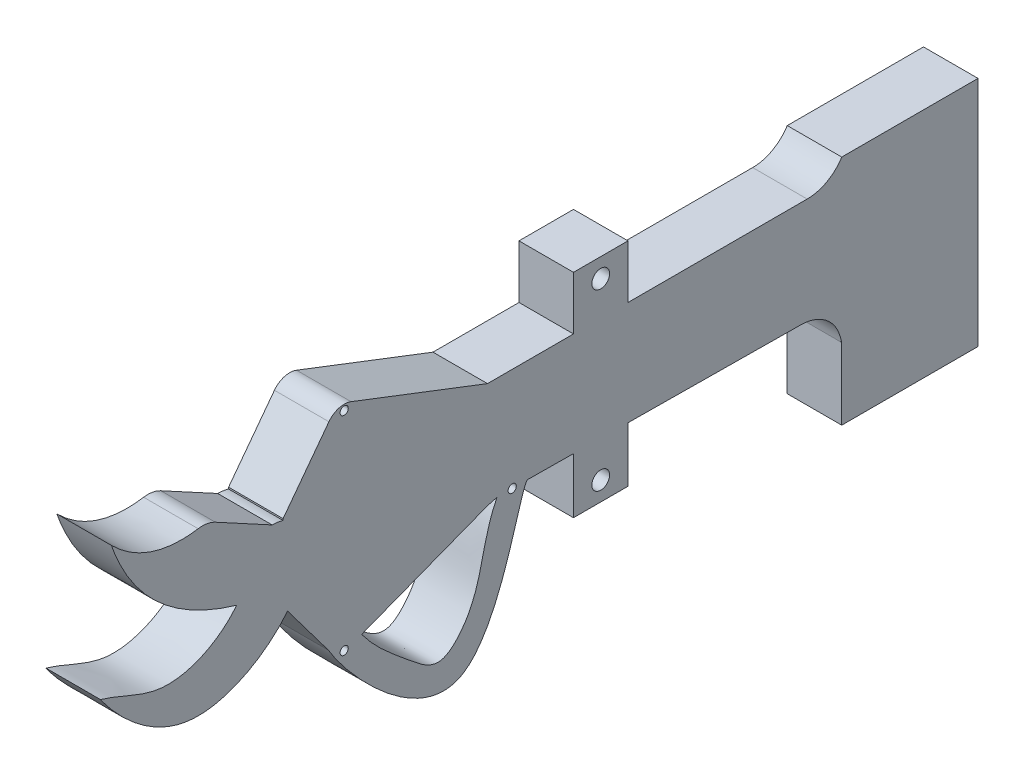
SolidWorks part; units mm, degrees
ref_plane "Front Plane" through (0, 0, 0) normal (0, 0, 1) x (1, 0, 0)
ref_plane "Top Plane" through (0, 0, 0) normal (0, 1, 0) x (1, 0, 0)
ref_plane "Right Plane" through (0, 0, 0) normal (1, 0, 0) x (0, 0, -1)
ref_plane "Plane4" through (70, 0, 0) normal (1, 0, 0) x (0, 0, -1)
sketch "Sketch15" plane through (70, 0, 0) normal (1, 0, 0) x (0, 0, -1)
  line L0 (-98.44, 39) -> (-98.44, -39)
  line L1 (-98.44, -39) -> (-78.44, -39)
  line L2 (0, -32.5439) -> (0, -58.81)
  line L3 (-78.44, -39) -> (-78.44, 39)
  line L4 (-78.44, 39) -> (-98.44, 39)
  line L5 (50, 26.41) -> (50, -58.81)
  line L6 (-88.44, 39) -> (-88.44, -39) construction
  line L7 (-229.8609, 25.2996) -> (-209, 14)
  line L8 (-205, -13.4164) -> (-205, -14)
  line L9 (-205, -14) -> (-203.3467, -16.1994)
  line L37 (0, 26.41) -> (50, 26.41)
  line L39 (50, -58.81) -> (0, -58.81)
  line L44 (0, -32.5439) -> (0, -32.1716)
  line L46 (-180.0653, 38.7034) -> (-130, 19.41)
  line L48 (-205, 14) -> (-188.1778, 36.3778)
  line L49 (-205, 13.4164) -> (-205, 14)
  line L50 (-205, -14) -> (-205, -13.4164)
  line L51 (-188.1778, -36.3778) -> (-205, -14)
  line L52 (-130, -19.41) -> (-180.0653, -38.7034)
  line L56 (-126.4914, -18.4594) -> (-122.4285, -18.4594)
  line L57 (-119.4285, -18.4594) -> (-115.3655, -18.4594)
  line L58 (-188.3397, -36.1623) -> (-188.1778, -36.3778)
  line L59 (-180.0653, -38.7034) -> (-176.1714, -37.2028)
  line L60 (-130, 19.41) -> (-12.6886, 19.41)
  line L61 (-115.3655, -18.4594) -> (-15, -19.41)
  line L63 (0, -32.1716) -> (0, -32.5439)
  line L64 (-130, -19.41) -> (-126.4914, -18.4594)
  circle A0 centre (-209, 0) radius 14
  circle A1 centre (-88.44, 32) radius 3.25
  circle A2 centre (-88.44, -32) radius 3.25
  circle A3 centre (-182.5824, 37.1303) radius 1.5
  circle A4 centre (-182.5824, -39.1197) radius 1.5
  arc A8 (-229.8609, 25.2996) -> (-236.1722, 26.3861) centre (-234.6237, 16.5067) ccw
  arc A10 (-181.0865, -39.0099) -> (-180.0653, -38.7034) centre (-182.5824, -32.1716) ccw
  circle A20 centre (-120.9285, -18.4594) radius 1.5
  arc A21 (-180.0653, 38.7034) -> (-184.5114, 38.9005) centre (-182.5824, 32.1716) ccw
  arc A22 (-184.5114, 38.9005) -> (-188.1778, 36.3778) centre (-182.5824, 32.1716) ccw
  arc A26 (-188.1778, -36.3778) -> (-184.0784, -39.0099) centre (-182.5824, -32.1716) ccw
  arc A27 (-181.0865, -39.0099) -> (-180.0653, -38.7034) centre (-182.5824, -32.1716) ccw
  arc A28 (-122.4285, -18.4594) -> (-119.4285, -18.4594) centre (-120.9285, -18.4594) ccw
  arc A29 (-188.1778, -36.3778) -> (-184.0784, -39.0099) centre (-182.5824, -32.1716) ccw
  parabola Q1 (-222.0767, -5) -> (-268, 37) focus (-233.1222, 34.7362) apex (-255.3029, 14.9374)
  spline S3 degree 3 poles (-268, 37) (-259.1388, 28.0952) (-248.2711, 24.4897) (-236.1722, 26.3861) knots 0 0 0 0 0.920407 0.920407 0.920407 0.920407
  spline S4 degree 3 poles (-272, -10) (-264.5451, -12.0829) (-248.031, -22.7664) (-228.2351, -13.0001) (-222.0767, -5) knots 0 0 0 0 0.427591 1 1 1 1
  spline S5 degree 3 poles (-203.3467, -16.1994) (-211.2266, -26.0808) (-240.3414, -42.6421) (-264.5448, -20.589) (-272, -10) knots 0 0 0 0 0.497871 1 1 1 1
  spline S10 degree 3 poles (-115.3655, -18.4594) (-118.3377, -20.6676) (-132.1424, -105.1833) (-182.5001, -46.5279) (-188.3397, -36.1623) knots 0.03269 0.03269 0.03269 0.03269 0.488323 0.982304 0.982304 0.982304 0.982304
  spline S11 degree 3 poles (-176.1714, -37.2028) (-171.1396, -44.05) (-162.8, -50.6114) (-148.0822, -63.1004) (-130.812, -46.5745) (-132.6764, -30.3522) (-126.4914, -18.4594) knots 0.06069 0.06069 0.06069 0.06069 0.334247 0.473196 0.580463 0.999066 0.999066 0.999066 0.999066
  spline S13 degree 3 poles (-12.6886, 19.41) (-7.65, 19.3515) (-2.6421, 22.1348) (0, 26.41) knots 0 0 0 0 1 1 1 1
  spline S14 degree 3 poles (-15, -19.41) (-13.2495, -19.4082) (-10.6365, -19.8734) (-7.2275, -21.4632) (-4.4307, -23.53) (-1.9381, -26.6201) (-0.6472, -29.848) (-0.1519, -31.8366) (0, -32.5439) knots 0 0 0 0 0.092791 0.138362 0.198535 0.275881 0.345018 0.382437 0.382437 0.382437 0.382437
  point P50 (-98.44, 0)
  dimension "D9" = 15.1247
  dimension "D2" = 28
  dimension "D15" = 21.7136
  dimension "D18" = 6.5
  dimension "D20" = 6.5
  dimension "D21" = 3
  dimension "D22" = 3
  dimension "D1" = 78
  dimension "D3" = 20
  dimension "D4" = 78
  dimension "D5" = 85.22
  dimension "D6" = 50
  dimension "D7" = 93.6345
  dimension "D8" = 117.3114
  dimension "D10" = 20.8222
  dimension "D11" = 32.8286
  dimension "D12" = 82.5086
  dimension "D13" = 63
  dimension "D14" = 100.37
  dimension "D16" = 138.44
  dimension "D17" = 7
  dimension "D19" = 7
  dimension "D23" = 76.25
extrude "Boss-Extrude15" add sketch "Sketch15" along normal blind 20 separate body
sketch "Sketch16" plane through (70, 0, 0) normal (-1, 0, 0) x (0, 0, 1)
  line L1 (277.9669, -76.6757) -> (-58.0331, -76.6757)
  line L2 (277.9669, -76.6757) -> (277.9669, 49.3243)
  line L3 (277.9669, 49.3243) -> (-58.0331, 49.3243)
  line L4 (-58.0331, -76.6757) -> (-58.0331, 49.3243)
  dimension "D1" = 336
  dimension "D2" = 126
